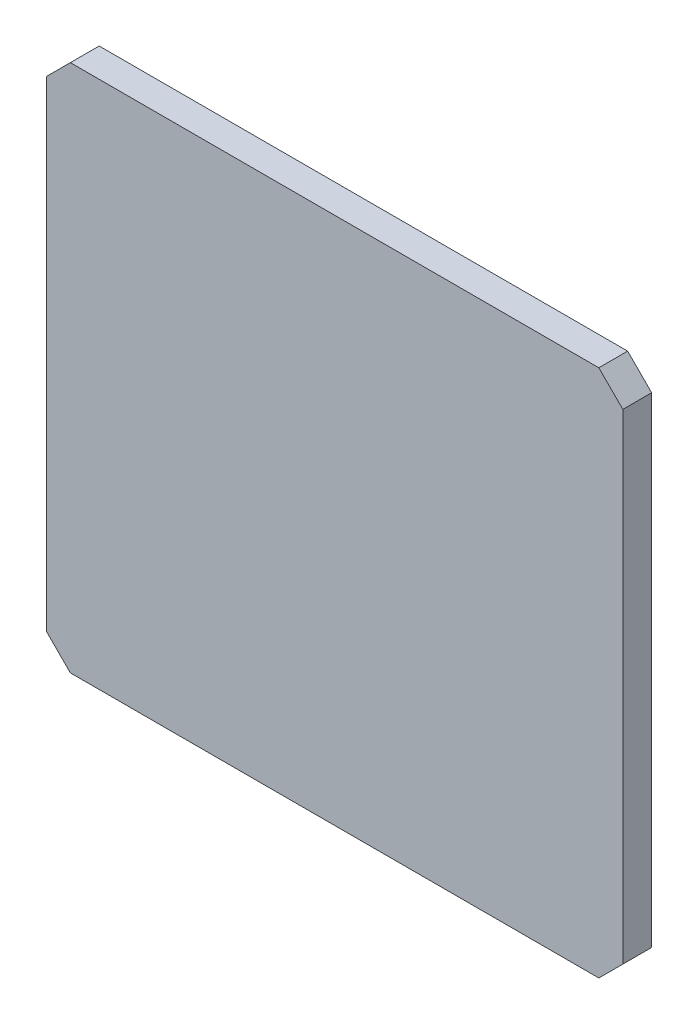
SolidWorks part; units mm, degrees
material "Vidrio"
ref_plane "Alzado" through (0, 0, 0) normal (0, 0, 1) x (1, 0, 0)
ref_plane "Planta" through (0, 0, 0) normal (0, 1, 0) x (1, 0, 0)
ref_plane "Vista lateral" through (0, 0, 0) normal (1, 0, 0) x (0, 0, -1)
sketch "Croquis1" plane through (0, 0, 0) normal (0, 0, 1) x (1, 0, 0)
  line L1 (-11.8671, 8.6542) -> (24.1329, 8.6542)
  line L2 (-11.8671, 8.6542) -> (-11.8671, -24.3458)
  line L3 (-11.8671, -24.3458) -> (24.1329, -24.3458)
  line L4 (24.1329, 8.6542) -> (24.1329, -24.3458)
  dimension "D1" = 36
  dimension "D2" = 33
extrude "Saliente-Extruir1" add sketch "Croquis1" along normal blind 1.8
chamfer "Chaflán1" distance 1.5 angle 45 4 edges at (24.1329, -24.3458, 0.9) (-11.8671, -24.3458, 0.9) (24.1329, 8.6542, 0.9) (-11.8671, 8.6542, 0.9)
